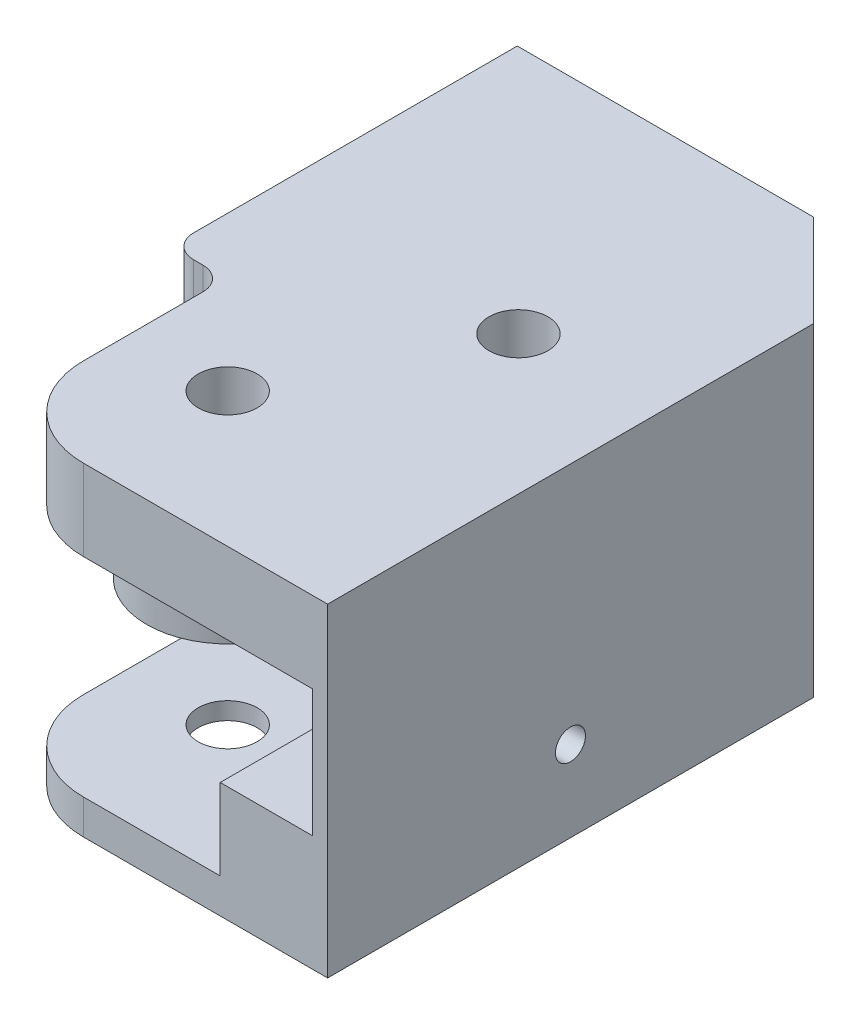
SolidWorks part; units mm, degrees
material "ABS"
ref_plane "Front" through (0, 0, 0) normal (0, 0, 1) x (1, 0, 0)
ref_plane "Top" through (0, 0, 0) normal (0, 1, 0) x (1, 0, 0)
ref_plane "Right" through (0, 0, 0) normal (1, 0, 0) x (0, 0, -1)
sketch "Эскиз1" plane through (0, 0, 0) normal (0, 1, 0) x (1, 0, 0)
  line L0 (8.8, 25) -> (-16.8, 25)
  line L1 (16.8, 17) -> (8.8, 25)
  line L2 (16.8, -25) -> (16.8, 17)
  line L3 (-16.8, 25) -> (-16.8, -3)
  line L4 (-14.8, -5) -> (-13.9793, -5)
  line L5 (-11.9793, -7) -> (-11.9793, -17.3431)
  line L6 (-4.3224, -25) -> (16.8, -25)
  circle A1 centre (4.8, 3.5) radius 2.55
  circle A2 centre (-3.4895, -13.3528) radius 2.55
  arc A4 (-16.8, -3) -> (-14.8, -5) centre (-14.8, -3) ccw
  arc A5 (-13.9793, -5) -> (-11.9793, -7) centre (-13.9793, -7) cw
  arc A6 (-11.9793, -17.3431) -> (-4.3224, -25) centre (-4.3224, -17.3431) ccw
  dimension "D2" = 5.1
extrude "Бобышка-Вытянуть1" add sketch "Эскиз1" along normal blind 3
sketch "Эскиз3" plane through (0, 3, 0) normal (0, 1, 0) x (1, 0, 0)
  line L7 (8.8, 25) -> (-16.8, 25)
  line L8 (16.8, 17) -> (8.8, 25)
  line L9 (16.8, -25) -> (16.8, 17)
  line L10 (-16.8, 25) -> (-16.8, -2.3528)
  line L13 (7.5105, -25) -> (16.8, -25)
  line L21 (-3.4895, -2.3528) -> (-16.8, -2.3528)
  line L22 (7.5105, -13.3528) -> (7.5105, -25)
  circle A7 centre (4.8, 3.5) radius 2.55
  arc A11 (7.5105, -13.3528) -> (-3.4895, -2.3528) centre (-3.4895, -13.3528) ccw
extrude "Бобышка-Вытянуть2" add sketch "Эскиз3" along normal blind 7
sketch "Эскиз4" plane through (0, 10, 0) normal (0, 1, 0) x (1, 0, 0)
  line L7 (8.8, 25) -> (-16.8, 25)
  line L8 (16.8, 17) -> (8.8, 25)
  line L9 (16.8, -25) -> (16.8, 17)
  line L10 (-16.8, 25) -> (-16.8, 14.5148)
  line L13 (15.5, -25) -> (16.8, -25)
  line L20 (5.0318, 14.5148) -> (-16.8, 14.5148)
  line L21 (15.5, -25) -> (15.5, 0.1212)
  line L22 (-16.8, 25) -> (-16.8, -2.3528) construction
  arc A8 (15.5, 0.1212) -> (5.0318, 14.5148) centre (5.0318, 3.5113) ccw
  dimension "D1" = 1.3
extrude "Бобышка-Вытянуть3" add sketch "Эскиз4" along normal blind 11
sketch "Эскиз5" plane through (0, 21, 0) normal (0, 1, 0) x (1, 0, 0)
  line L7 (8.8, 25) -> (-16.8, 25)
  line L8 (16.8, 17) -> (8.8, 25)
  line L9 (16.8, -25) -> (16.8, 17)
  line L10 (-16.8, 25) -> (-16.8, -3)
  line L11 (-14.8, -5) -> (-13.9793, -5)
  line L12 (-11.9793, -7) -> (-11.9793, -23)
  line L13 (-9.9793, -25) -> (16.8, -25)
  circle A7 centre (4.8, 3.5) radius 2.55
  circle A8 centre (-3.4895, -13.3528) radius 2.55
  arc A9 (-11.9793, -23) -> (-9.9793, -25) centre (-9.9793, -23) ccw
  arc A10 (-16.8, -3) -> (-14.8, -5) centre (-14.8, -3) ccw
  arc A11 (-13.9793, -5) -> (-11.9793, -7) centre (-13.9793, -7) cw
extrude "Бобышка-Вытянуть4" add sketch "Эскиз5" along normal blind 7
sketch "Эскиз6" plane through (0, 21, 0) normal (0, -1, 0) x (1, 0, 0)
  circle A0 centre (-3.4895, 13.3528) radius 2.55
  circle A1 centre (-3.4895, 13.3528) radius 7
extrude "Бобышка-Вытянуть5" add sketch "Эскиз6" along normal blind 7
sketch "Эскиз7" plane through (0, 0, -25) normal (0, 0, -1) x (-1, 0, 0)
  circle A0 centre (4, 13.75) radius 1.3
extrude "Вырез-Вытянуть1" cut sketch "Эскиз7" against normal blind 5
sketch "Эскиз8" plane through (16.8, 0, 0) normal (1, 0, 0) x (0, 0, -1)
  line L0 (-25, 0) -> (17, 0) construction
  circle A0 centre (-4, 7) radius 1.3
  point P5 (-4, 0)
  dimension "D1" = 7
extrude "Вырез-Вытянуть2" cut sketch "Эскиз8" against normal blind 5
sketch "Эскиз9" plane through (0, 0, 0) normal (0, -1, 0) x (1, 0, 0)
  circle A0 centre (-3.4895, 13.3528) radius 5
  circle A1 centre (4.8, -3.5) radius 5
extrude "Вырез-Вытянуть3" cut sketch "Эскиз9" against normal blind 1.5
sketch "Эскиз10" plane through (0, 21, 0) normal (0, -1, 0) x (1, 0, 0)
  line L0 (-4.3224, 25) -> (-11.9793, 25)
  line L1 (-11.9793, 25) -> (-11.9793, 17.3431)
  arc A0 (-4.3224, 25) -> (-11.9793, 17.3431) centre (-4.3224, 17.3431) ccw
extrude "Вырез-Вытянуть4" cut sketch "Эскиз10" against normal up to next
fillet "Скругление1" radius 2 1 edges at (-3.4895, 21, 20.3528)
